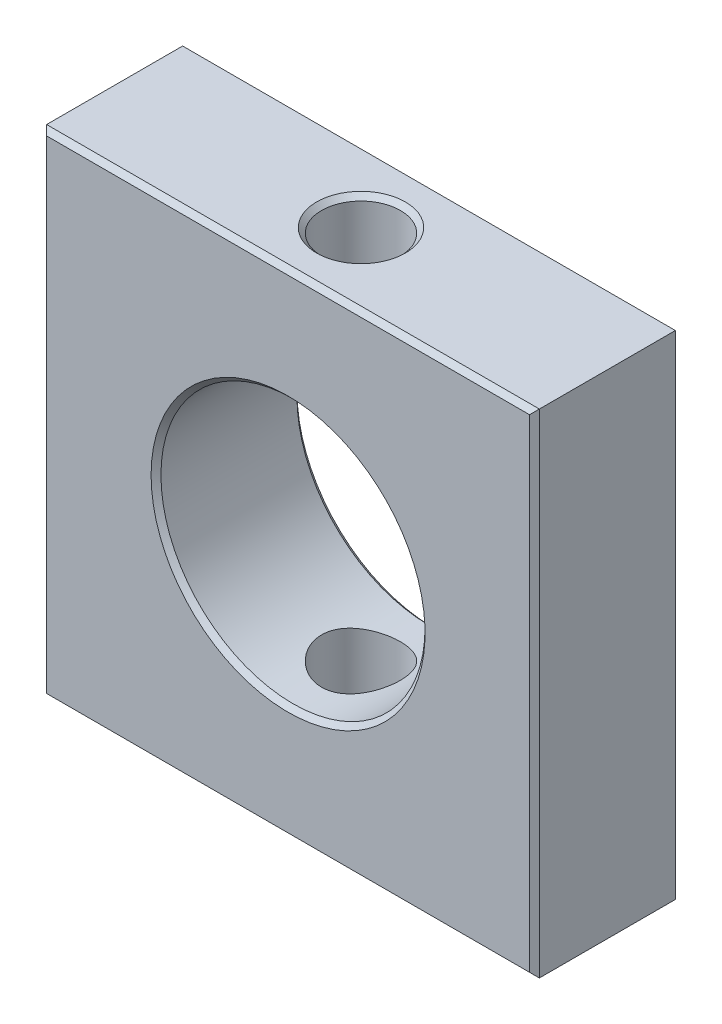
SolidWorks part; units mm, degrees
ref_plane "Front Plane" through (0, 0, 0) normal (0, 0, 1) x (1, 0, 0)
ref_plane "Top Plane" through (0, 0, 0) normal (0, 1, 0) x (1, 0, 0)
ref_plane "Right Plane" through (0, 0, 0) normal (1, 0, 0) x (0, 0, -1)
sketch "Sketch1" plane through (0, 0, 0) normal (0, 0, 1) x (1, 0, 0)
  line L0 (0, 11.646) -> (0, -12.2344) construction
  line L1 (-16.0837, 0) -> (19.3691, 0) construction
  line L3 (-12.5, -12.5) -> (12.5, -12.5)
  line L4 (-12.5, -12.5) -> (-12.5, 12.5)
  line L5 (-12.5, 12.5) -> (12.5, 12.5)
  line L6 (12.5, -12.5) -> (12.5, 12.5)
  line L7 (-12.5, -12.5) -> (12.5, 12.5) construction
  line L8 (-12.5, 12.5) -> (12.5, -12.5) construction
  circle A0 centre (0, 0) radius 6.7
  dimension "D1" = 13.4
  dimension "D2" = 25
  dimension "D3" = 25
extrude "Boss-Extrude1" add sketch "Sketch1" along normal blind 7.4
sketch "Sketch2" plane through (0, 0, 0) normal (0, 1, 0) x (1, 0, 0)
  line L0 (0, 3.8547) -> (0, -9.1116) construction
  line L1 (-11.959, -7.4) -> (12.602, -7.4) construction
  circle A0 centre (0, -3.7) radius 2
  dimension "D2" = 4
  dimension "D3" = 3.7
  dimension "D1" = 7.4
extrude "Cut-Extrude1" cut sketch "Sketch2" against normal through all both and the other way through all
chamfer "Chamfer1" distance 0.25 angle 45 12 edges at (6.7, 0, 7.4) (0, -12.5, 7.4) (-12.5, 0, 7.4) (0, 12.5, 7.4) (12.5, 0, 7.4) (6.7, 0, 0) (0, 12.5, 0) (-12.5, 0, 0) (0, -12.5, 0) (12.5, 0, 0) (0, -12.5, 5.7) (0, 12.5, 5.7)
